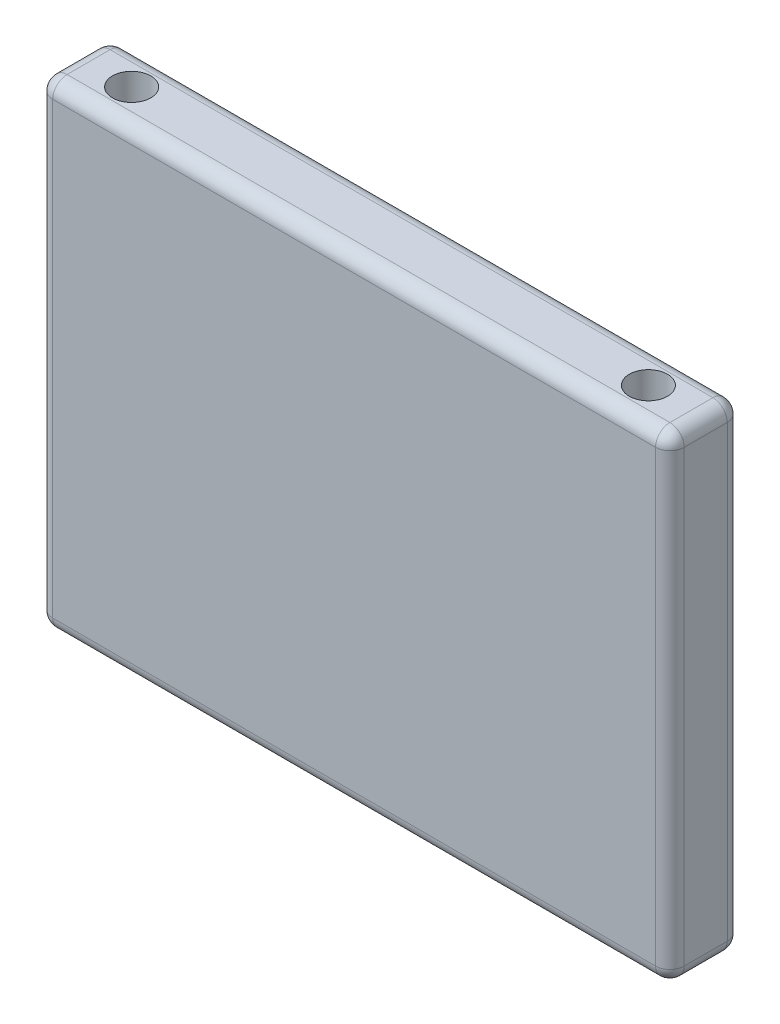
SolidWorks part; units mm, degrees
ref_plane "Front Plane" through (0, 0, 0) normal (0, 0, 1) x (1, 0, 0)
ref_plane "Top Plane" through (0, 0, 0) normal (0, 1, 0) x (1, 0, 0)
ref_plane "Right Plane" through (0, 0, 0) normal (1, 0, 0) x (0, 0, -1)
sketch "Sketch1" plane through (0, 0, 0) normal (0, 0, 1) x (1, 0, 0)
  line L5 (-66.0661, 50) -> (66.0661, 50)
  line L6 (-66.0661, 50) -> (-66.0661, -50)
  line L7 (-66.0661, -50) -> (66.0661, -50)
  line L8 (66.0661, 50) -> (66.0661, -50)
  line L9 (-66.0661, 50) -> (66.0661, -50) construction
  line L10 (-66.0661, -50) -> (66.0661, 50) construction
  point P0 (0, 0)
  dimension "D1" = 100
extrude "Boss-Extrude1" add sketch "Sketch1" along normal blind 15
sketch "Sketch2" plane through (0, -50, 0) normal (0, -1, 0) x (1, 0, 0)
  line L0 (-66.0661, 15) -> (-66.0661, 0) construction
  line L1 (-66.0661, 15) -> (66.0661, 15) construction
  line L2 (0, 0) -> (0, 31.2871) construction
  circle A0 centre (-54.0661, 7.5) radius 4
  circle A1 centre (54.0661, 7.5) radius 4
  dimension "D3" = 8
  dimension "D1" = 12
  dimension "D2" = 7.5
extrude "Cut-Extrude1" cut sketch "Sketch2" against normal blind 20
mirror "Mirror1" about plane through (0, 0, 0) normal (0, 1, 0) of "Cut-Extrude1"
fillet "Fillet1" radius 3 12 edges at (-66.0661, 50, 7.5) (0, 50, 0) (0, 50, 15) (66.0661, 50, 7.5) (66.0661, 0, 0) (66.0661, -50, 7.5) (66.0661, 0, 15) (0, -50, 0) (-66.0661, 0, 0) (-66.0661, 0, 15) (-66.0661, -50, 7.5) (0, -50, 15)
